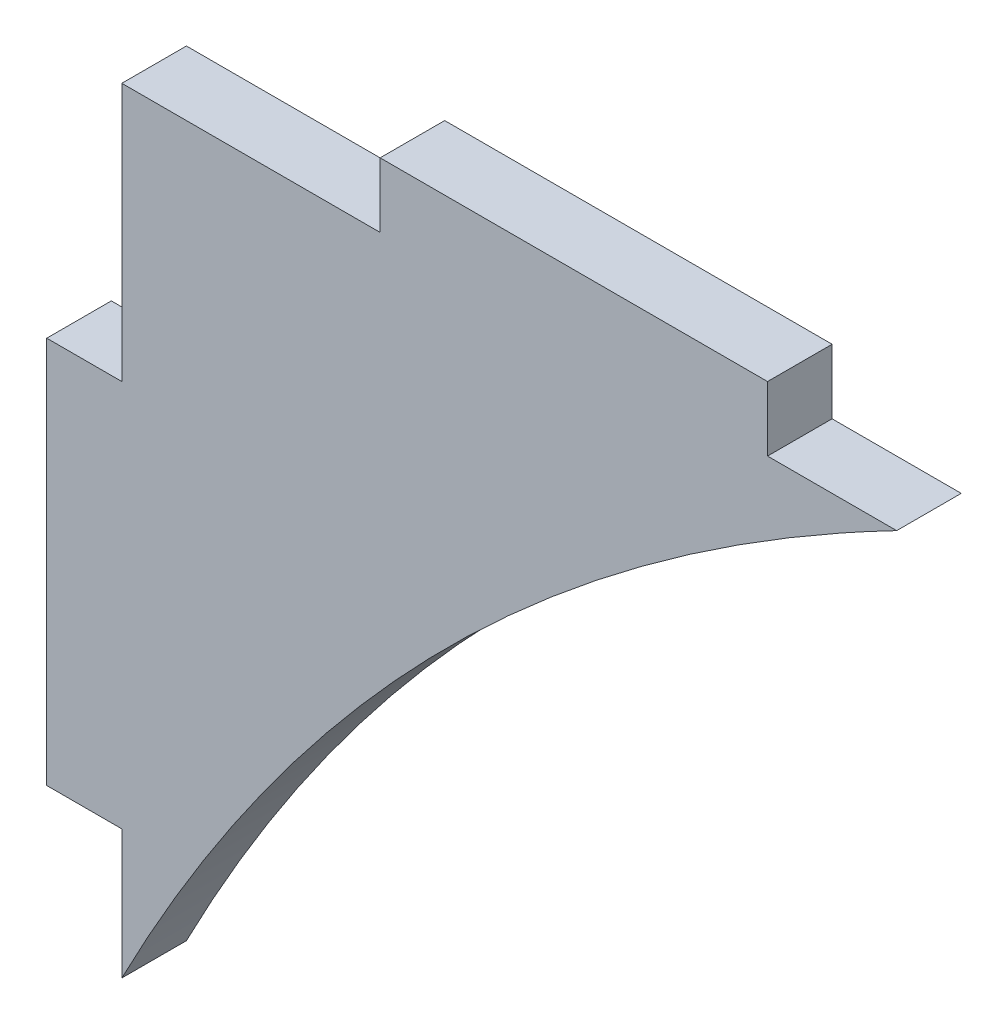
SolidWorks part; units mm, degrees
ref_plane "Front Plane" through (0, 0, 0) normal (0, 0, 1) x (1, 0, 0)
ref_plane "Top Plane" through (0, 0, 0) normal (0, 1, 0) x (1, 0, 0)
ref_plane "Right Plane" through (0, 0, 0) normal (1, 0, 0) x (0, 0, -1)
sketch "Sketch1" plane through (0, 0, 0) normal (0, 0, 1) x (1, 0, 0)
  line L0 (-31.3311, -8.6105) -> (-31.3311, -13.6105)
  line L1 (-31.3311, 16.3895) -> (-21.3311, 16.3895)
  line L2 (-31.3311, 16.3895) -> (-31.3311, 6.3895)
  line L5 (-21.3311, 18.8895) -> (-6.3311, 18.8895)
  line L6 (-21.3311, 18.8895) -> (-21.3311, 16.3895)
  line L8 (-6.3311, 18.8895) -> (-6.3311, 16.3895)
  line L9 (-31.3311, 6.3895) -> (-34.238, 6.3895)
  line L10 (-6.3311, 16.3895) -> (-1.3311, 16.3895)
  line L11 (-31.3311, -8.6105) -> (-34.238, -8.6105)
  line L12 (-34.238, 6.3895) -> (-34.238, -8.6105)
  spline S0 degree 2 poles (-31.3311, -13.6105) (-21.0828, 6.1913) (-1.3311, 16.3895) knots 0 0 0 1 1 1
  dimension "D1" = 2.5
  dimension "D2" = 15
  dimension "D4" = 30
  dimension "D5" = 10
  dimension "D6" = 15
  dimension "D7" = 10
extrude "Boss-Extrude1" add sketch "Sketch1" along normal blind 2.5 contours L1 L6 L5 L8 L10 S0 L0 L11 L12 L9 L2
